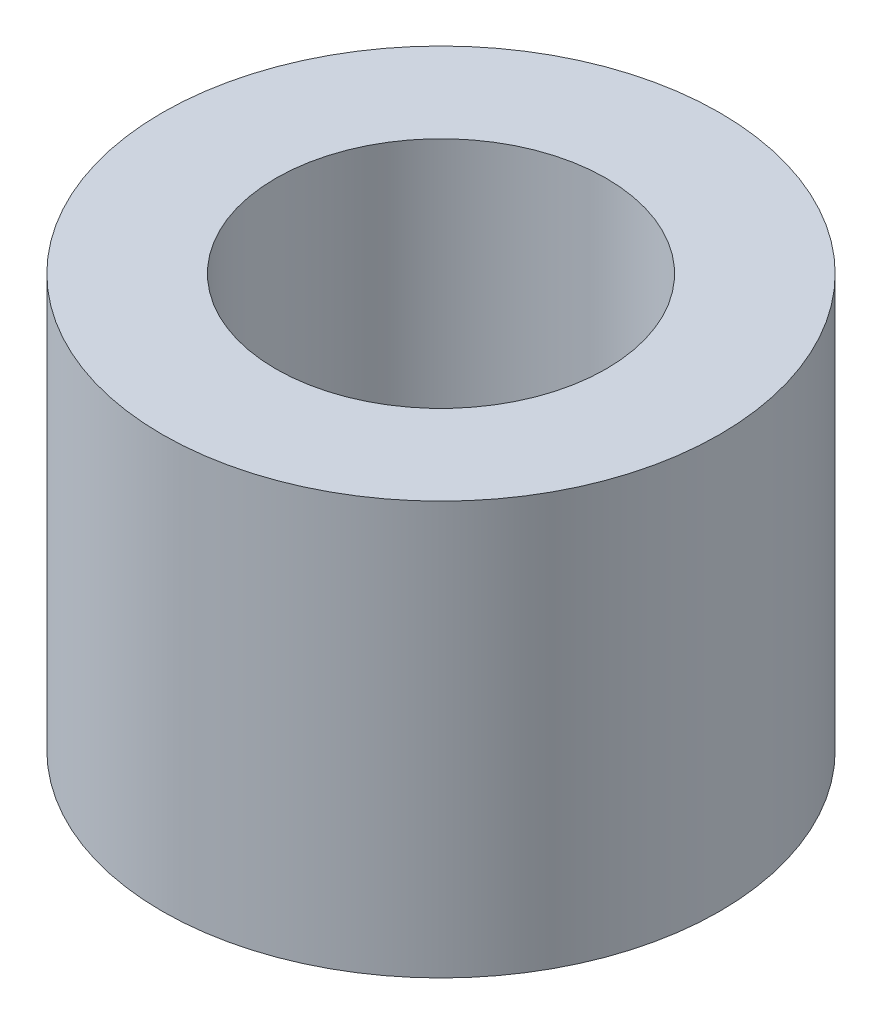
SolidWorks part; units mm, degrees
material "尼龙 101"
ref_plane "前视基准面" through (0, 0, 0) normal (0, 0, 1) x (1, 0, 0)
ref_plane "上视基准面" through (0, 0, 0) normal (0, 1, 0) x (1, 0, 0)
ref_plane "右视基准面" through (0, 0, 0) normal (1, 0, 0) x (0, 0, -1)
other "Configuration Table"
sketch "草图1" plane through (0, 0, 0) normal (0, 1, 0) x (1, 0, 0)
  circle A0 centre (0, 0) radius 1.6
  circle A1 centre (0, 0) radius 2.7
  dimension "D1" = 3.2
  dimension "D2" = 5.4
extrude "凸台-拉伸1" add sketch "草图1" along normal blind 4
